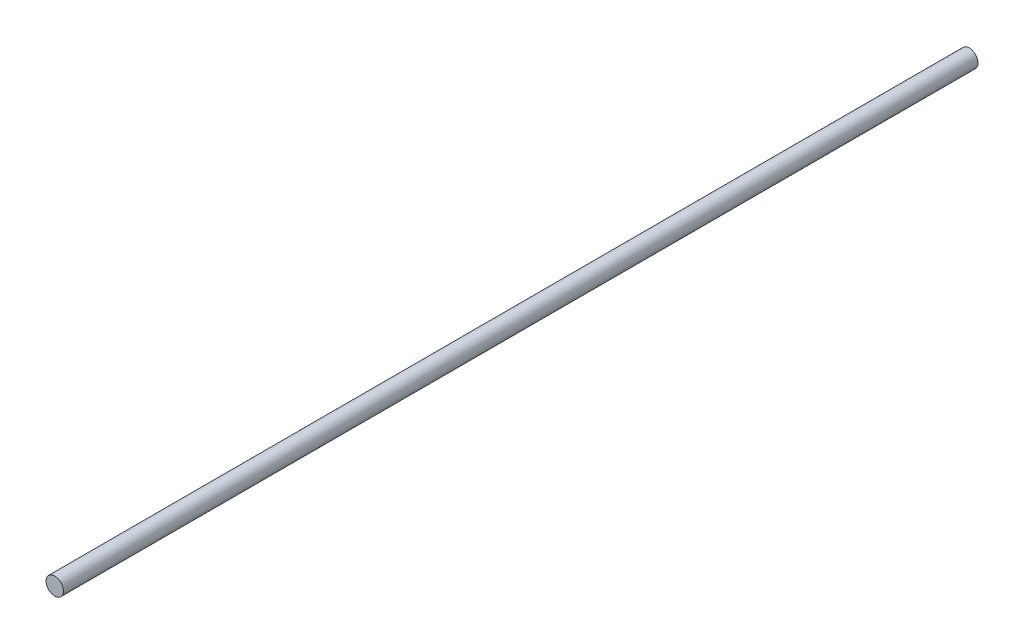
SolidWorks part; units mm, degrees
ref_plane "Front Plane" through (0, 0, 0) normal (0, 0, 1) x (1, 0, 0)
ref_plane "Top Plane" through (0, 0, 0) normal (0, 1, 0) x (1, 0, 0)
ref_plane "Right Plane" through (0, 0, 0) normal (1, 0, 0) x (0, 0, -1)
sketch "Sketch1" plane through (0, 0, 0) normal (0, 0, 1) x (1, 0, 0)
  circle A0 centre (0, 0) radius 7.9375
  dimension "D1" = 15.875
extrude "Boss-Extrude1" add sketch "Sketch1" along normal blind 831.85
